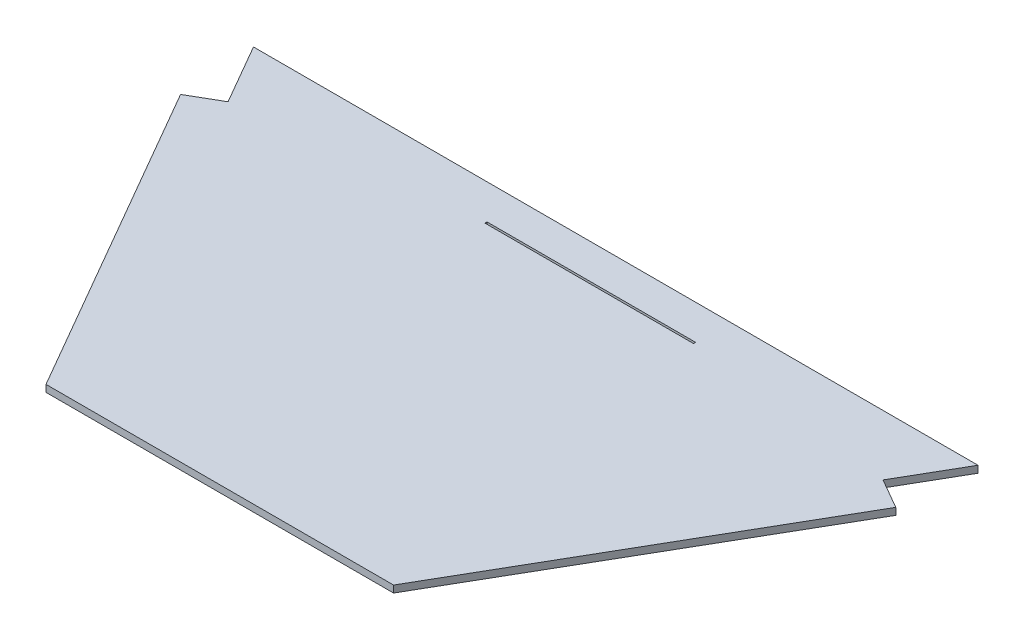
SolidWorks part; units mm, degrees
material "Ti-6Al-4VSolution treated and aged (SS)"
ref_plane "Front Plane" through (0, 0, 0) normal (0, 0, 1) x (1, 0, 0)
ref_plane "Top Plane" through (0, 0, 0) normal (0, 1, 0) x (1, 0, 0)
ref_plane "Right Plane" through (0, 0, 0) normal (1, 0, 0) x (0, 0, -1)
sketch "Sketch1" plane through (0, 0, 0) normal (0, 1, 0) x (1, 0, 0)
  line L1 (-271.1337, 569.6174) -> (771.1337, 569.6174)
  line L3 (500, 0) -> (0, 0)
  line L4 (0, 0) -> (-264.435, 458.0149)
  line L5 (-264.435, 458.0149) -> (-221.1337, 483.0149)
  line L6 (-221.1337, 483.0149) -> (-271.1337, 569.6174)
  line L7 (500, 0) -> (764.435, 458.0149)
  line L8 (764.435, 458.0149) -> (721.1337, 483.0149)
  line L9 (721.1337, 483.0149) -> (771.1337, 569.6174)
  dimension "D2" = 500
  dimension "D3" = 120
  dimension "D4" = 120
  dimension "D6" = 528.87
  dimension "D9" = 50
  dimension "D10" = 100
extrude "Boss-Extrude1" add sketch "Sketch1" along normal blind 10
sketch "Sketch2" plane through (0, 0, 0) normal (0, -1, 0) x (1, 0, 0)
  line L0 (414.88, -519.62) -> (114.88, -519.62)
  line L1 (114.88, -519.62) -> (114.88, -516.62)
  line L2 (114.88, -516.62) -> (414.88, -516.62)
  line L3 (414.88, -516.62) -> (414.88, -519.62)
  line L4 (0, 0) -> (500, 0) construction
  dimension "D1" = 516.62
  dimension "D2" = 3
  dimension "D3" = 300
  dimension "D4" = 114.88
extrude "Cut-Extrude1" cut sketch "Sketch2" against normal through all
